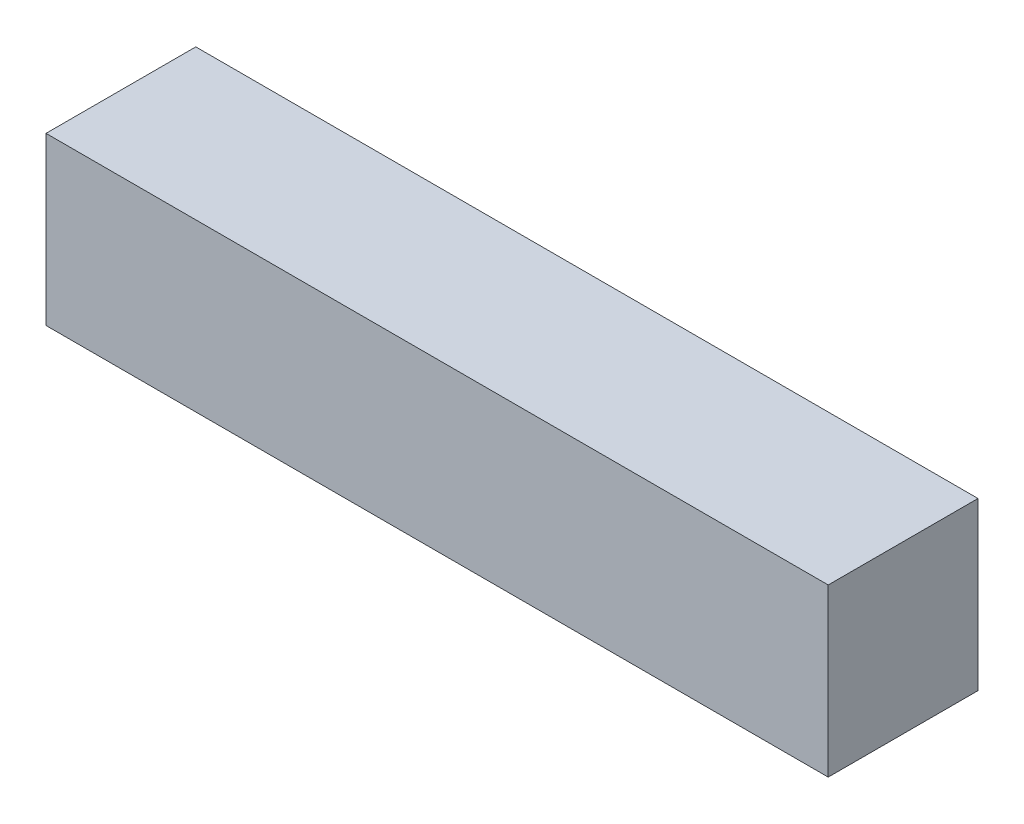
SolidWorks part; units mm, degrees
ref_plane "Front" through (0, 0, 0) normal (0, 0, 1) x (1, 0, 0)
ref_plane "Top" through (0, 0, 0) normal (0, 1, 0) x (1, 0, 0)
ref_plane "Right" through (0, 0, 0) normal (1, 0, 0) x (0, 0, -1)
sketch "Sketch1" plane through (0, 0, 0) normal (0, 1, 0) x (1, 0, 0)
  line L1 (0, 0) -> (47, 0)
  line L2 (0, 0) -> (0, 9)
  line L3 (0, 9) -> (47, 9)
  line L4 (47, 0) -> (47, 9)
  dimension "D1" = 47
  dimension "D2" = 9
extrude "Boss-Extrude1" add sketch "Sketch1" along normal blind 10
